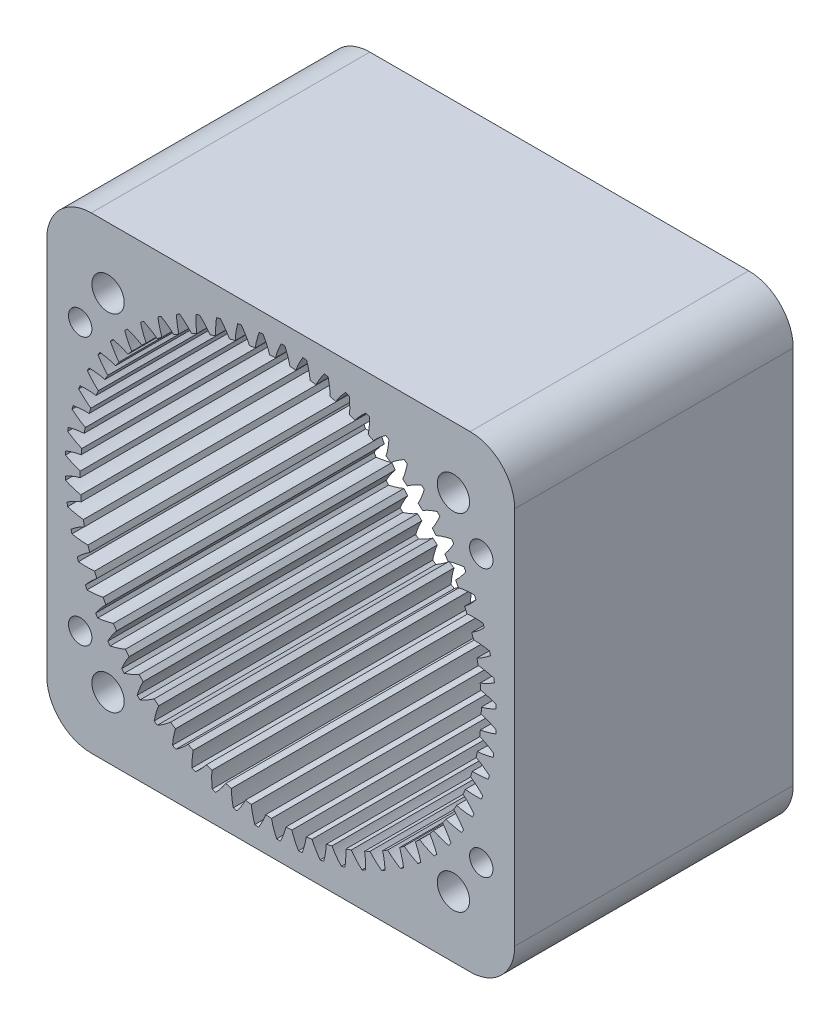
SolidWorks part; units mm, degrees
other "标注1"
sketch "草图9" plane through (-21, -21, 36) normal (-0.2153, -0.0648, 0.9744) x (0.3119, -0.9501, 0.0057)
other "标注2"
sketch "草图20" plane through (-30, -30, 20) normal (-0.0347, -0.0183, 0.9992) x (0.9994, -0.0065, 0.0346)
other "标注3"
sketch "草图27" plane through (-23.5298, 22.2328, 18) normal (-0.0197, 0.0107, 0.9997) x (0.9998, 0.0061, 0.0196)
ref_plane "前视基准面" through (0, 0, 0) normal (0, 0, 1) x (1, 0, 0)
ref_plane "上视基准面" through (0, 0, 0) normal (0, 1, 0) x (1, 0, 0)
ref_plane "右视基准面" through (0, 0, 0) normal (1, 0, 0) x (0, 0, -1)
sketch "草图1" plane through (0, 0, 0) normal (0, 0, 1) x (1, 0, 0)
  line L5 (-17.2128, -17.2128) -> (24.7872, 24.7872) construction
  line L6 (-21, 21) -> (21, -21) construction
  line L7 (21, 21) -> (-21, 21)
  line L8 (21, 21) -> (21, -21)
  line L9 (21, -21) -> (-21, -21)
  line L10 (-21, 21) -> (-21, -21)
  line L11 (0, -21) -> (0, 21) construction
  line L12 (21, 0) -> (-21, 0) construction
  circle A9 centre (0, 0) radius 30 construction
  circle A30 centre (15.5, 15.5) radius 1.55 construction
  circle A31 centre (15.5, -15.5) radius 1.55 construction
  circle A32 centre (-15.5, -15.5) radius 1.55 construction
  circle A33 centre (-15.5, 15.5) radius 1.55 construction
  point P31 (0, 0)
  point P37 (0, 0)
  point P48 (0, 0)
  dimension "D1" = 42
  dimension "D4" = 60
  dimension "D6" = 42
  dimension "D2" = 15.5
  dimension "D3" = 15.5
  dimension "D9" = 3.1
  dimension "D10" = 4
extrude "凸台-拉伸1" add sketch "草图1" along normal blind 25 contours L7 L10 L9 L8 A33 A32 A31 A30
sketch "草图6" plane through (0, 0, 0) normal (0, 0, 1) x (1, 0, 0)
  line L0 (0, 0) -> (17.4783, 0) construction
  line L1 (0, 0) -> (35.0568, 1.4114) construction
  line L2 (0, 0) -> (18.5979, 0.2772) construction
  circle A0 centre (0, 0) radius 18.6 construction
  circle A1 centre (0, 0) radius 5 construction
  circle A2 centre (0, 0) radius 17.4783 construction
  circle A3 centre (0, 0) radius 19.35 construction
  arc A4 (18.3136, -3.2516) -> (18.5979, 0.2772) centre (0, 0) cw construction
  circle A5 centre (0, 0) radius 10
  circle A7 centre (0, 0) radius 18
  arc A8 (19.3266, 0.951) -> (19.3404, 0.6105) centre (0, 0) cw
  spline S0 degree 4 poles (17.4783, 0) (17.4925, 0.0003) (17.5322, 0.0022) (17.607, 0.0095) (17.7287, 0.0269) (17.9531, 0.0708) (18.219, 0.1425) (18.5148, 0.2419) (18.8271, 0.3668) (19.0904, 0.4849) (19.3492, 0.6127) (19.6033, 0.7493) (19.9061, 0.9251) (20.2627, 1.1511) (20.668, 1.4349) (21.1151, 1.7826) (21.5533, 2.1589) (21.9735, 2.5535) (22.3775, 2.9674) (22.7628, 3.3942) (23.1343, 3.8408) (23.4399, 4.2347) (23.6995, 4.5935) (23.8967, 4.8761) (24.0713, 5.1411) (24.2387, 5.3961) (24.5035, 5.8331) (24.6633, 6.1083) (24.9023, 6.5423) (24.9838, 6.7039) (25.0508, 6.8322) knots 0 0 0 0 0 0.005377 0.015084 0.028532 0.04661 0.092111 0.119476 0.146842 0.174209 0.201575 0.228941 0.256307 0.307035 0.361767 0.4165 0.471232 0.525964 0.580697 0.635429 0.690161 0.744894 0.77226 0.799626 0.826992 0.854358 0.909091 0.954545 1 1 1 1 1 construction
  spline S1 degree 4 poles (17.4783, 0) (17.4925, 0.0003) (17.5322, 0.0022) (17.607, 0.0095) (17.7287, 0.0269) (17.9531, 0.0708) (18.219, 0.1425) (18.5148, 0.2419) (18.8271, 0.3668) (19.0904, 0.4849) (19.3492, 0.6127) (19.6033, 0.7493) (19.9061, 0.9251) (20.2627, 1.1511) (20.668, 1.4349) (21.1151, 1.7826) (21.5533, 2.1589) (21.9735, 2.5535) (22.3775, 2.9674) (22.7628, 3.3942) (23.1343, 3.8408) (23.4399, 4.2347) (23.6995, 4.5935) (23.8967, 4.8761) (24.0713, 5.1411) (24.2387, 5.3961) (24.4258, 5.7049) (24.5246, 5.8715) (24.5902, 5.985) knots 0 0 0 0 0 0.005377 0.015084 0.028532 0.04661 0.092111 0.119476 0.146842 0.174209 0.201575 0.228941 0.256307 0.307035 0.361767 0.4165 0.471232 0.525964 0.580697 0.635429 0.690161 0.744894 0.77226 0.799626 0.826992 0.854358 0.909091 0.909091 0.909091 0.909091 0.909091
  spline S2 degree 4 poles (17.2013, 1.4625) (17.2171, 1.4634) (17.2615, 1.4649) (17.3455, 1.4635) (17.4824, 1.4551) (17.7362, 1.4264) (18.0386, 1.3704) (18.3767, 1.2863) (18.7356, 1.1753) (19.0393, 1.0676) (19.3387, 0.9485) (19.6338, 0.8192) (19.9867, 0.6508) (20.4039, 0.4312) (20.8804, 0.1518) (21.4093, -0.1951) (21.9308, -0.5747) (22.4339, -0.9761) (22.9208, -1.4006) (23.388, -1.841) (23.8416, -2.3047) (24.2171, -2.7157) (24.5382, -3.0918) (24.7831, -3.3886) (25.0013, -3.6679) (25.2104, -3.9367) (25.4464, -4.2636) (25.5714, -4.4402) (25.6545, -4.5607) knots 0 0 0 0 0 0.005377 0.015084 0.028532 0.04661 0.092111 0.119476 0.146842 0.174209 0.201575 0.228941 0.256307 0.307035 0.361767 0.4165 0.471232 0.525964 0.580697 0.635429 0.690161 0.744894 0.77226 0.799626 0.826992 0.854358 0.909091 0.909091 0.909091 0.909091 0.909091
  point P6 (30.6834, 1.2647)
  dimension "D1" = 37.2
  dimension "D2" = 10
  dimension "D3" = 38.7
  dimension "D4" = 34.9566
  dimension "D6" = 36
  dimension "D7" = 20
  dimension "D5" = 1.452
extrude "切除-拉伸1" cut sketch "草图6" along normal through all
pattern_circular "阵列(圆周)1" count 62 over 360 about axis through (0, 0, 0) along (0, 0, -1) of "切除-拉伸1"
fillet "圆角2" radius 4 4 edges at (21, -21, 12.5) (-21, -21, 12.5) (-21, 21, 12.5) (21, 21, 12.5)
sketch "草图23" plane through (0, 0, 0) normal (0, 0, -1) x (-1, 0, 0)
  line L0 (-21, 17) -> (-21, -17) construction
  line L1 (-21, 13) -> (-17, 13)
  line L2 (-21, 13) -> (-21, 9)
  line L5 (-17, 21) -> (17, 21) construction
  line L18 (-21, 9) -> (-17, 13)
  line L19 (9, 21) -> (13, 17)
  line L20 (13, 21) -> (13, 17)
  line L21 (13, 21) -> (9, 21)
  line L22 (21, -9) -> (17, -13)
  line L23 (21, -13) -> (17, -13)
  line L24 (21, -13) -> (21, -9)
  line L25 (-9, -21) -> (-13, -17)
  line L26 (-13, -21) -> (-13, -17)
  line L27 (-13, -21) -> (-9, -21)
  point P19 (0, 0)
  point P23 (-7, 0)
  dimension "D1" = 4
  dimension "D2" = 4
  dimension "D3" = 8
  dimension "D4" = 4
extrude "切除-拉伸14" [suppressed] cut sketch "草图23" against normal blind 3
sketch "草图24" plane through (0, 0, 25) normal (0, 0, 1) x (1, 0, 0)
  line L0 (-21, 13) -> (-17, 13)
  line L1 (-21, 13) -> (-21, 9)
  line L16 (-21, 17) -> (-21, -17) construction
  line L17 (17, 21) -> (-17, 21) construction
  line L30 (-21, 9) -> (-17, 13)
  line L40 (9, 21) -> (13, 17)
  line L41 (13, 21) -> (13, 17)
  line L42 (13, 21) -> (9, 21)
  line L43 (21, -9) -> (17, -13)
  line L44 (21, -13) -> (17, -13)
  line L45 (21, -13) -> (21, -9)
  line L46 (-9, -21) -> (-13, -17)
  line L47 (-13, -21) -> (-13, -17)
  line L48 (-13, -21) -> (-9, -21)
  point P16 (0.2043, -0.1277)
  point P20 (0.2043, -0.1277)
  point P21 (0, 0)
  point P24 (-7, 0)
  dimension "D1" = 4
  dimension "D2" = 4
  dimension "D3" = 8
  dimension "D4" = 4
extrude "切除-拉伸15" [suppressed] cut sketch "草图24" against normal blind 4
sketch "草图25" plane through (0, 0, 25) normal (0, 0, 1) x (1, 0, 0)
  line L0 (17, 21) -> (-17, 21) construction
  line L1 (-21, 17) -> (-21, -17) construction
  line L2 (0, 22.2328) -> (0, -23.0812) construction
  line L3 (-23.5298, 0) -> (36.1925, 0) construction
  circle A0 centre (-18, 12) radius 1.05
  circle A1 centre (18, 12) radius 1.05
  circle A2 centre (18, -12) radius 1.05
  circle A3 centre (-18, -12) radius 1.05
  dimension "D1" = 2.1
  dimension "D2" = 9
  dimension "D3" = 3
extrude "切除-拉伸16" cut sketch "草图25" against normal through all
sketch "草图28" plane through (0, 0, 25) normal (0, 0, 1) x (1, 0, 0)
  line L0 (-23.5298, 0) -> (36.1925, 0) construction
  line L1 (0, 22.2328) -> (0, -23.0812) construction
  circle A0 centre (-15.5, 15.5) radius 1.45
  circle A1 centre (15.5, 15.5) radius 1.45
  circle A2 centre (15.5, -15.5) radius 1.45
  circle A3 centre (-15.5, -15.5) radius 1.45
  point P15 (0, 0)
  dimension "D1" = 2.9
  dimension "D2" = 15.5
  dimension "D3" = 15.5
  dimension "D4" = 4
extrude "切除-拉伸17" cut sketch "草图28" against normal blind 8
sketch "草图29" plane through (0, 0, 0) normal (0, 0, -1) x (-1, 0, 0)
  line L2 (-16.9706, 16.9706) -> (0, 0) construction
  line L3 (0, 22.2328) -> (0, -23.0812) construction
  circle A0 centre (-16.9706, 16.9706) radius 2.1
  circle A1 centre (16.9706, 16.9706) radius 2.1
  circle A2 centre (16.9706, -16.9706) radius 2.1
  circle A3 centre (-16.9706, -16.9706) radius 2.1
  point P12 (0, 0)
  dimension "D4" = 4.2
  dimension "D1" = 24
  dimension "D3" = 45
  dimension "D2" = 4
extrude "切除-拉伸18" cut sketch "草图29" against normal blind 8
equation "\"m\"= 0.6"
equation "\"z\"= 62"
equation "\"a\"= 20"
equation "\"d\"= \"m\" * \"z\""
equation "\"da\"= \"m\" * ( \"z\" - 2 )"
equation "\"df\"= \"d\" + 2.5 * \"m\""
equation "\"db\"= \"d\" * cos ( \"a\" )"
equation "\"s\"= pi * \"m\" / 2"
equation "\"D1@草图6\"=\"d\""
equation "\"D3@草图6\"=\"df\""
equation "\"D4@草图6\"=\"db\""
equation "\"D6@草图6\"=\"da\""
equation "\"sr\"= 360 / \"z\" / 4"
equation "\"D5@草图6\"=\"sr\""
equation "\"D1@阵列(圆周)1\"=\"z\""
